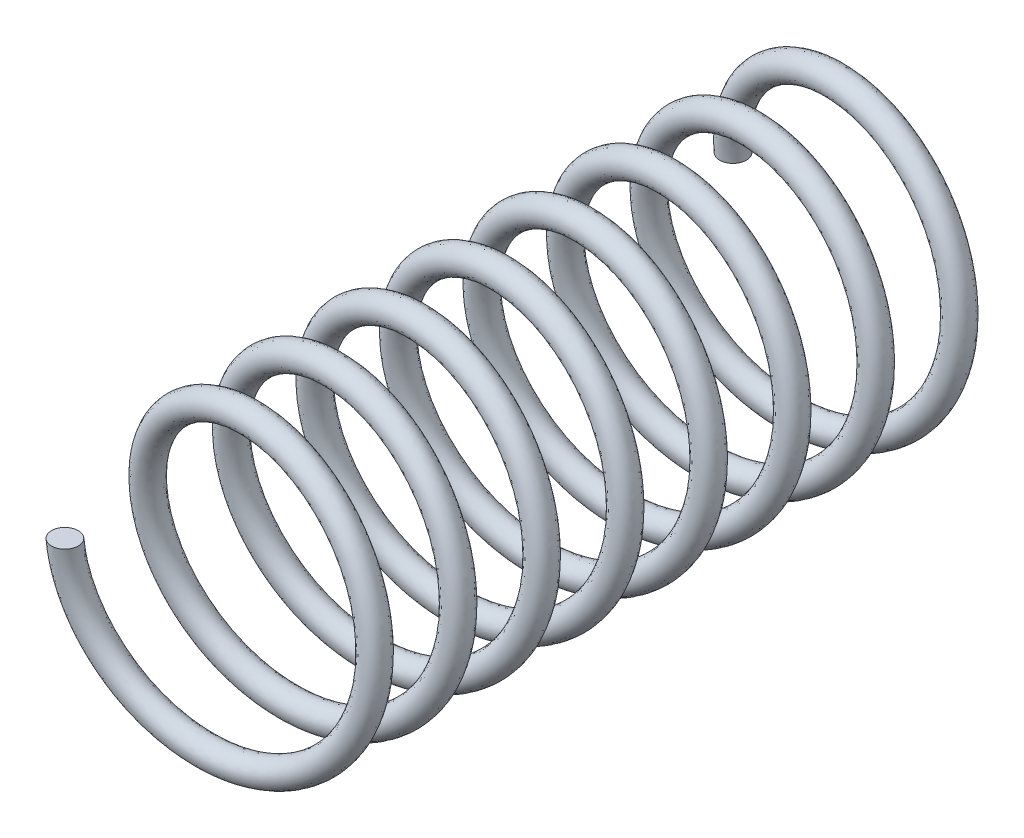
SolidWorks part; units mm, degrees
ref_plane "Piano frontale" through (0, 0, 0) normal (0, 0, 1) x (1, 0, 0)
ref_plane "Piano superiore" through (0, 0, 0) normal (0, 1, 0) x (1, 0, 0)
ref_plane "Piano destro" through (0, 0, 0) normal (1, 0, 0) x (0, 0, -1)
sketch "Schizzo1" plane through (0, 0, 0) normal (0, 0, 1) x (1, 0, 0)
  circle A0 centre (0, 0) radius 10
  dimension "D1" = 20
curve "Elica/Spirale1" pitch 6.25 height 50 turns 8
sketch "Schizzo2" plane through (0, 0, 0) normal (0, 1, 0) x (1, 0, 0)
  circle A0 centre (-10, 0) radius 1
  spline S0 degree 3 poles (-10, 0) (-10, -0.1294) (-9.4793, -0.391) (-7.2552, -0.7811) (-3.9265, -1.1719) (0, -1.5625) (3.9265, -1.9531) (7.2552, -2.3437) (9.4793, -2.7344) (10.2603, -3.125) (9.4793, -3.5156) (7.2552, -3.9062) (2.8169, -4.4271) (-2.8169, -4.9479) (-7.2552, -5.4687) (-9.4793, -5.8594) (-10.2603, -6.25) (-9.4793, -6.6406) (-7.2552, -7.0312) (-2.8169, -7.5521) (2.8169, -8.0729) (7.2552, -8.5937) (9.4793, -8.9844) (10.2603, -9.375) (9.4793, -9.7656) (7.2552, -10.1563) (2.8169, -10.6771) (-2.8169, -11.1979) (-7.2552, -11.7188) (-9.4793, -12.1094) (-10.2603, -12.5) (-9.4793, -12.8906) (-7.2552, -13.2813) (-2.8169, -13.8021) (2.8169, -14.3229) (7.2552, -14.8438) (9.4793, -15.2344) (10.2603, -15.625) (9.4793, -16.0156) (7.2552, -16.4062) (2.8169, -16.9271) (-2.8169, -17.4479) (-7.2552, -17.9687) (-9.4793, -18.3594) (-10.2603, -18.75) (-9.4793, -19.1406) (-7.2552, -19.5312) (-2.8169, -20.0521) (2.8169, -20.5729) (7.2552, -21.0937) (9.4793, -21.4844) (10.2603, -21.875) (9.4793, -22.2656) (7.2552, -22.6562) (2.8169, -23.1771) (-2.8169, -23.6979) (-7.2552, -24.2187) (-9.4793, -24.6094) (-10.2603, -25) (-9.4793, -25.3906) (-7.2552, -25.7812) (-2.8169, -26.3021) (2.8169, -26.8229) (7.2552, -27.3437) (9.4793, -27.7344) (10.2603, -28.125) (9.4793, -28.5156) (7.2552, -28.9062) (2.8169, -29.4271) (-2.8169, -29.9479) (-7.2552, -30.4687) (-9.4793, -30.8594) (-10.2603, -31.25) (-9.4793, -31.6406) (-7.2552, -32.0312) (-2.8169, -32.5521) (2.8169, -33.0729) (7.2552, -33.5937) (9.4793, -33.9844) (10.2603, -34.375) (9.4793, -34.7656) (7.2552, -35.1562) (2.8169, -35.6771) (-2.8169, -36.1979) (-7.2552, -36.7187) (-9.4793, -37.1094) (-10.2603, -37.5) (-9.4793, -37.8906) (-7.2552, -38.2812) (-2.8169, -38.8021) (2.8169, -39.3229) (7.2552, -39.8437) (9.4793, -40.2344) (10.2603, -40.625) (9.4793, -41.0156) (7.2552, -41.4062) (2.8169, -41.9271) (-2.8169, -42.4479) (-7.2552, -42.9687) (-9.4793, -43.3594) (-10.2603, -43.75) (-9.4793, -44.1406) (-7.2552, -44.5313) (-2.8169, -45.0521) (2.8169, -45.5729) (7.2552, -46.0938) (9.4793, -46.4844) (10.2603, -46.875) (9.4793, -47.2656) (7.2552, -47.6563) (3.9265, -48.0469) (0, -48.4375) (-3.9265, -48.8281) (-7.2552, -49.2189) (-9.4793, -49.609) (-10, -49.8706) (-10, -50) knots 0 0 0 0 0.007813 0.015625 0.023438 0.03125 0.039063 0.046875 0.054688 0.0625 0.070313 0.078125 0.085938 0.101563 0.109375 0.117188 0.125 0.132813 0.140625 0.148438 0.164063 0.171875 0.179688 0.1875 0.195313 0.203125 0.210938 0.226563 0.234375 0.242188 0.25 0.257813 0.265625 0.273438 0.289063 0.296875 0.304688 0.3125 0.320313 0.328125 0.335938 0.351563 0.359375 0.367188 0.375 0.382813 0.390625 0.398438 0.414063 0.421875 0.429688 0.4375 0.445312 0.453125 0.460938 0.476562 0.484375 0.492187 0.5 0.507812 0.515625 0.523438 0.539063 0.546875 0.554688 0.5625 0.570313 0.578125 0.585938 0.601563 0.609375 0.617188 0.625 0.632813 0.640625 0.648438 0.664063 0.671875 0.679688 0.6875 0.695313 0.703125 0.710938 0.726563 0.734375 0.742188 0.75 0.757813 0.765625 0.773438 0.789063 0.796875 0.804688 0.8125 0.820313 0.828125 0.835938 0.851563 0.859375 0.867188 0.875 0.882813 0.890625 0.898438 0.914063 0.921875 0.929688 0.9375 0.945313 0.953125 0.960938 0.96875 0.976562 0.984375 0.992187 1 1 1 1 construction
  point P4 (0, 0)
  point P5 (0, 0)
  dimension "D1" = 2
sweep "Sweep1" add profiles "Schizzo2" path "Elica/Spirale1"
ref_plane "Piano1" through (0, 0, -1) normal (0, 0, 1) x (1, 0, 0)
ref_plane "Piano2" through (0, 0, 51) normal (0, 0, 1) x (1, 0, 0)
sketch "Schizzo3" plane through (0, 0, 0) normal (0, 0, 1) x (1, 0, 0)
  line L0 (-11, 0) -> (10.926, 0) construction
  line L1 (-11, 0) -> (-9, 0) construction
  line L2 (0, -11.0261) -> (0, 11.1178) construction
sketch "Schizzo4" plane through (0, 0, 0) normal (1, 0, 0) x (0, 0, -1)
  line L0 (0, 0) -> (-57.4585, 0) construction
